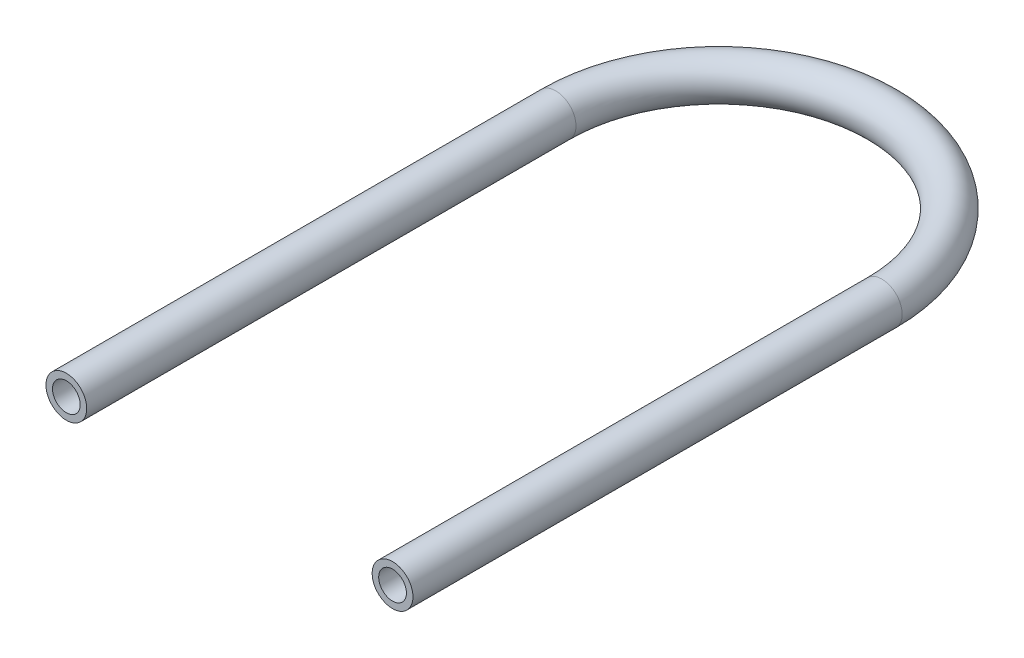
SolidWorks part; units mm, degrees
material "Copper"
ref_plane "Front Plane" through (0, 0, 0) normal (0, 0, 1) x (1, 0, 0)
ref_plane "Top Plane" through (0, 0, 0) normal (0, 1, 0) x (1, 0, 0)
ref_plane "Right Plane" through (0, 0, 0) normal (1, 0, 0) x (0, 0, -1)
sketch "Sketch3" plane through (0, 0, 0) normal (0, 1, 0) x (1, 0, 0)
  line L0 (-25.4, 0) -> (-25.4, 76.2)
  line L1 (25.4, 0) -> (25.4, 76.2)
  arc A0 (-25.4, 76.2) -> (25.4, 76.2) centre (0, 76.2) cw
  dimension "D4" = 25.4
  dimension "D1" = 76.2
  dimension "D2" = 25.4
  dimension "D3" = 50.8
sketch "Sketch4" plane through (0, 0, 0) normal (0, 0, 1) x (1, 0, 0)
  circle A0 centre (-25.4, 0) radius 3.175
  circle A1 centre (-25.4, 0) radius 2.159
  dimension "D1" = 6.35
  dimension "D2" = 4.318
sweep "Sweep1" add profiles "Sketch4" path "Sketch3"
